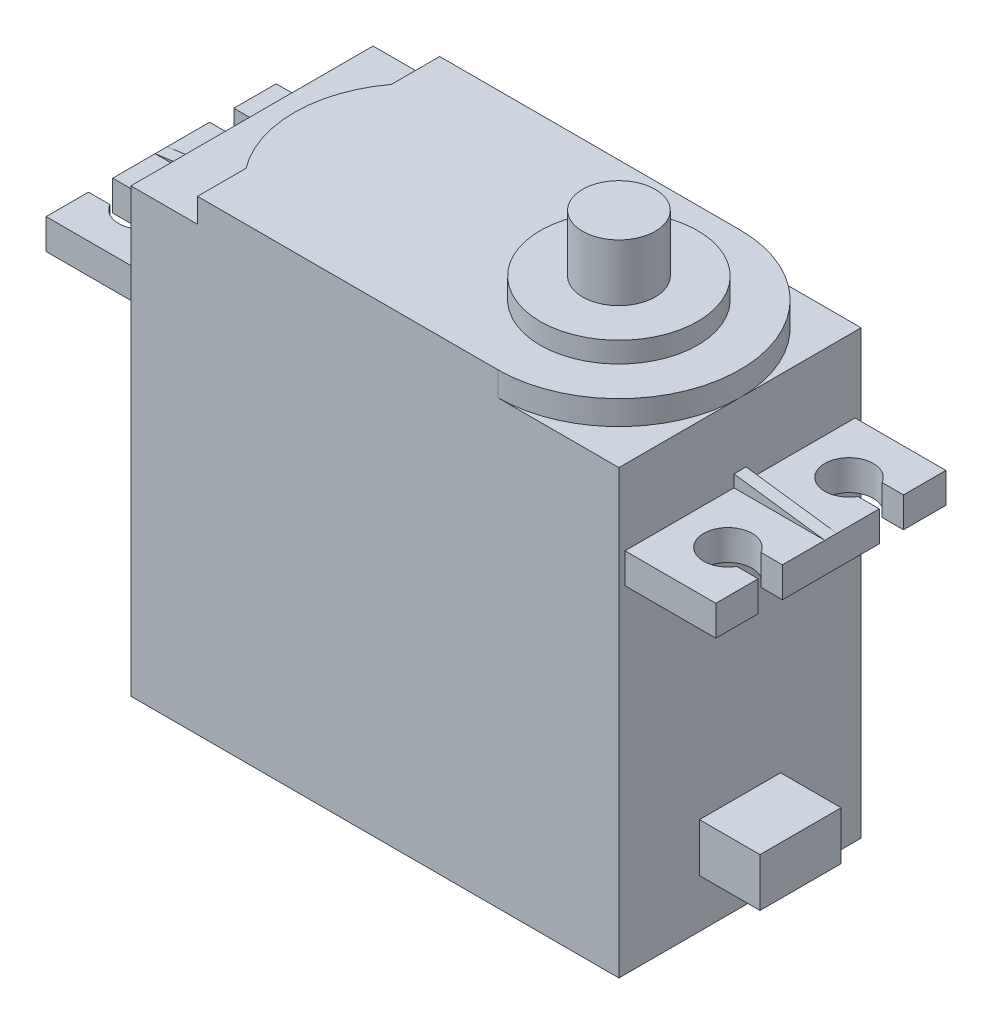
SolidWorks part; units mm, degrees
ref_plane "Front Plane" through (0, 0, 0) normal (0, 0, 1) x (1, 0, 0)
ref_plane "Top Plane" through (0, 0, 0) normal (0, 1, 0) x (1, 0, 0)
ref_plane "Right Plane" through (0, 0, 0) normal (1, 0, 0) x (0, 0, -1)
sketch "Sketch1" plane through (0, 0, 0) normal (0, 1, 0) x (1, 0, 0)
  line L1 (0, 0) -> (40.3, 0)
  line L2 (0, 0) -> (0, 20)
  line L3 (0, 20) -> (40.3, 20)
  line L4 (40.3, 0) -> (40.3, 20)
  dimension "D1" = 20
  dimension "D2" = 40.3
extrude "Boss-Extrude1" add sketch "Sketch1" along normal blind 36.5
sketch "Sketch2" plane through (0, 0, 0) normal (-1, 0, 0) x (0, 0, 1)
  line L0 (-20, 36.5) -> (-20, 0) construction
  line L1 (-19.5, 30.3) -> (-0.5, 30.3)
  line L2 (-19.5, 30.3) -> (-19.5, 27.8)
  line L3 (-19.5, 27.8) -> (-0.5, 27.8)
  line L4 (-0.5, 30.3) -> (-0.5, 27.8)
  line L5 (-20, 36.5) -> (0, 36.5) construction
  dimension "D1" = 2.5
  dimension "D2" = 19
  dimension "D3" = 0.5
  dimension "D4" = 6.2
extrude "Boss-Extrude2" add sketch "Sketch2" along normal blind 7.5 and the other way blind 47.8
sketch "Sketch3" plane through (0, 30.3, 0) normal (0, 1, 0) x (1, 0, 0)
  line L0 (40.3, 0.5) -> (40.3, 19.5) construction
  line L1 (47.8, 0.5) -> (40.3, 0.5) construction
  line L2 (47.8, 0.5) -> (47.8, 19.5) construction
  line L3 (47.8, 4) -> (45.8, 4)
  line L4 (47.8, 4) -> (47.8, 6)
  line L5 (47.8, 6) -> (45.8, 6)
  line L6 (45.8, 4) -> (45.8, 6)
  line L7 (47.8, 16) -> (45.8, 16)
  line L8 (47.8, 14) -> (47.8, 16)
  line L9 (47.8, 14) -> (45.8, 14)
  line L10 (45.8, 14) -> (45.8, 16)
  line L11 (20.15, 20) -> (20.15, 0) construction
  line L12 (40.3, 20) -> (0, 20) construction
  line L13 (0, 0) -> (40.3, 0) construction
  line L14 (-5.5, 14) -> (-5.5, 16)
  line L15 (-7.5, 14) -> (-5.5, 14)
  line L16 (-7.5, 14) -> (-7.5, 16)
  line L17 (-7.5, 16) -> (-5.5, 16)
  line L18 (-5.5, 4) -> (-5.5, 6)
  line L19 (-7.5, 6) -> (-5.5, 6)
  line L20 (-7.5, 4) -> (-7.5, 6)
  line L21 (-7.5, 4) -> (-5.5, 4)
  circle A0 centre (44.3, 5) radius 2
  circle A1 centre (44.3, 15) radius 2
  circle A2 centre (-4, 15) radius 2
  circle A3 centre (-4, 5) radius 2
  line M3 (47.8, 0.5) -> (47.8, 19.5)
  dimension "D1" = 4
  dimension "D2" = 4
  dimension "D3" = 4
  dimension "D4" = 4
  dimension "D5" = 10
  dimension "D6" = 4.5
  dimension "D7" = 2
  dimension "D8" = 1
  dimension "D9" = 2
  dimension "D10" = 2
extrude "Cut-Extrude1" cut sketch "Sketch3" against normal blind 7.5 contours A2 L17 L14 L15 | L15 A2 L17 L16 | L21 A3 L19 L20 | A3 L19 L18 L21 | A3 L21 L18 L19 | A2 L15 L14 L17 | L7 A1 L9 L10 | A1 L9 L7 M3 | L9 A1 L7 L10 | L5 A0 L3 L6 | A0 L3 L5 M3 | L3 A0 L5 L6
sketch "Sketch5" plane through (0, 30.3, 0) normal (0, 1, 0) x (1, 0, 0)
  line L0 (47.8, 6) -> (47.8, 14) construction
  line L1 (47.8, 10.5) -> (40.3, 10.5)
  line L2 (47.8, 10.5) -> (47.8, 9.5)
  line L3 (47.8, 9.5) -> (40.3, 9.5)
  line L4 (40.3, 10.5) -> (40.3, 9.5)
  line L5 (40.3, 0.5) -> (40.3, 19.5) construction
  line L6 (0, 20) -> (0, 0) construction
  line L7 (0, 10.5) -> (-7.5, 10.5)
  line L8 (0, 10.5) -> (0, 9.5)
  line L9 (0, 9.5) -> (-7.5, 9.5)
  line L10 (-7.5, 10.5) -> (-7.5, 9.5)
  line L11 (-7.5, 6) -> (-7.5, 14) construction
  line L12 (0, 19.5) -> (-7.5, 19.5) construction
  line L13 (47.8, 19.5) -> (40.3, 19.5) construction
  dimension "D1" = 1
  dimension "D2" = 1
  dimension "D3" = 9
  dimension "D4" = 9
extrude "Boss-Extrude3" add sketch "Sketch5" along normal blind 1
sketch "Sketch6" plane through (0, 0, -9.5) normal (0, 0, 1) x (1, 0, 0)
  line L0 (0, 31.3) -> (-7.5, 30.3)
  line L1 (-7.5, 30.3) -> (47.8, 30.3)
  line L2 (47.8, 30.3) -> (40.3, 31.3)
  line L4 (40.3, 31.3) -> (47.8, 31.3)
  line L5 (40.3, 31.3) -> (40.3, 30.3)
  line L6 (40.3, 30.3) -> (47.8, 30.3)
  line L7 (47.8, 31.3) -> (47.8, 30.3)
  line L8 (0, 31.3) -> (-7.5, 31.3)
  line L9 (0, 31.3) -> (0, 30.3)
  line L10 (0, 30.3) -> (-7.5, 30.3)
  line L11 (-7.5, 31.3) -> (-7.5, 30.3)
  line M2 (47.8, 30.3) -> (47.8, 31.3)
  line M3 (47.8, 31.3) -> (40.3, 31.3)
extrude "Cut-Extrude2" cut sketch "Sketch6" against normal blind 1 contours L8 L11 L0 | L2 M2 M3
sketch "Sketch7" plane through (0, 36.5, 0) normal (0, 1, 0) x (1, 0, 0)
  line L0 (40.3, 10) -> (30.3, 10) construction
  line L1 (40.3, 0) -> (40.3, 20) construction
  line L2 (40.3, 20) -> (0, 20) construction
  line L3 (0, 0) -> (40.3, 0) construction
  line L4 (0, 20) -> (0, 0) construction
  line L5 (5.5, 20) -> (30.3, 20)
  line L6 (5.5, 20) -> (5.5, 0)
  line L7 (5.5, 0) -> (30.3, 0)
  line L8 (30.3, 20) -> (30.3, 0)
  line L9 (0, 10) -> (13.5, 10) construction
  arc A0 (30.3, 20) -> (30.3, 0) centre (30.3, 10) cw
  arc A1 (13.5, 20) -> (13.5, 0) centre (13.5, 10) ccw
  line M2 (0, 0) -> (40.3, 0)
  line M4 (40.3, 20) -> (0, 20)
  dimension "D1" = 10
  dimension "D2" = 5.5
  dimension "D3" = 13.5
extrude "Boss-Extrude4" add sketch "Sketch7" along normal blind 2 contours A1 L6 L7 L8 M4 | L6 A1 | A1 L5 L6 | A1 L6 M2 | A0 L8
sketch "Sketch8" plane through (0, 38.5, 0) normal (0, 1, 0) x (1, 0, 0)
  circle A0 centre (30.3, 10) radius 6.5
  dimension "D1" = 13
extrude "Boss-Extrude5" add sketch "Sketch8" along normal blind 1.7
sketch "Sketch9" plane through (0, 40.2, 0) normal (0, 1, 0) x (1, 0, 0)
  circle A0 centre (30.3, 10) radius 3
  dimension "D1" = 6
extrude "Boss-Extrude6" add sketch "Sketch9" along normal blind 4.7
sketch "Sketch10" plane through (40.3, 0, 0) normal (1, 0, 0) x (0, 0, -1)
  line L0 (0, 0) -> (20, 0) construction
  line L1 (13.35, 8) -> (6.65, 8)
  line L2 (13.35, 8) -> (13.35, 4)
  line L3 (13.35, 4) -> (6.65, 4)
  line L4 (6.65, 8) -> (6.65, 4)
  point P8 (10, 0)
  dimension "D1" = 4
  dimension "D2" = 4
  dimension "D3" = 6.7
  dimension "D4" = 3.35
extrude "Boss-Extrude7" add sketch "Sketch10" along normal blind 5
